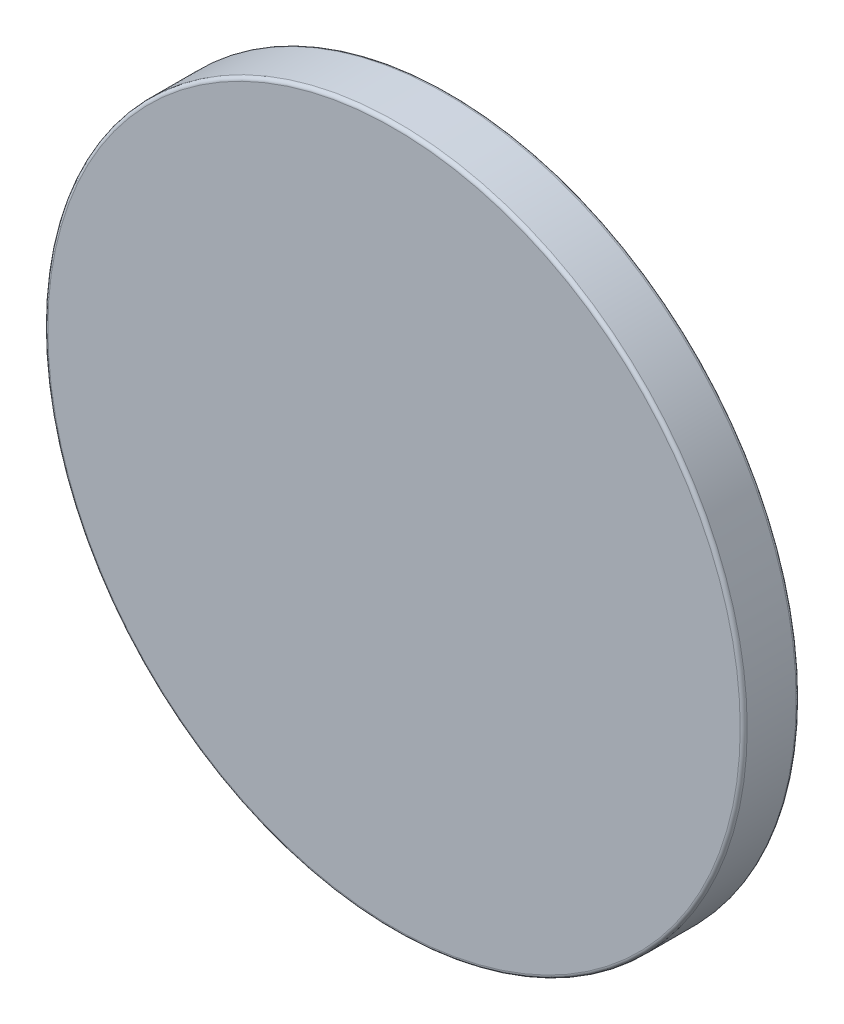
SolidWorks part; units mm, degrees
ref_plane "Front Plane" through (0, 0, 0) normal (0, 0, 1) x (1, 0, 0)
ref_plane "Top Plane" through (0, 0, 0) normal (0, 1, 0) x (1, 0, 0)
ref_plane "Right Plane" through (0, 0, 0) normal (1, 0, 0) x (0, 0, -1)
sketch "Sketch1" plane through (0, 0, 0) normal (0, 0, 1) x (1, 0, 0)
  circle A0 centre (0, 0) radius 12.7 construction
  dimension "OD" = 25.4
sketch "Sketch2" plane through (0, 0, 0) normal (1, 0, 0) x (0, 0, -1)
  line L0 (-1.016, 0) -> (1.016, 0) construction
  line L1 (0, 12.7) -> (0, -12.7) construction
  line L3 (-1.016, 12.7) -> (1.016, 12.7)
  line L4 (-1.016, 12.7) -> (-1.016, -12.7)
  line L5 (-1.016, -12.7) -> (1.016, -12.7)
  line L6 (1.016, 12.7) -> (1.016, -12.7)
  point P4 (0, 0)
  point P12 (0, 12.7)
  dimension "Thickness" = 2.032
sketch "Sketch3" plane through (0, 0, 0) normal (0, 0, 1) x (1, 0, 0)
  circle A0 centre (0, 0) radius 12.7 construction
  circle A1 centre (0, 0) radius 12.7
extrude "Boss-Extrude1" add sketch "Sketch3" along normal up to vertex (1.016 mm away) and the other way up to vertex (1.016 mm away) up to point (0, 12.7, 1.016) other way up to point (0, 12.7, -1.016)
fillet "Fillet1" radius 0.127 2 edges at (12.7, 0, -1.016) (12.7, 0, 1.016)
equation "\"Fillet@Fillet1\"=.005"
